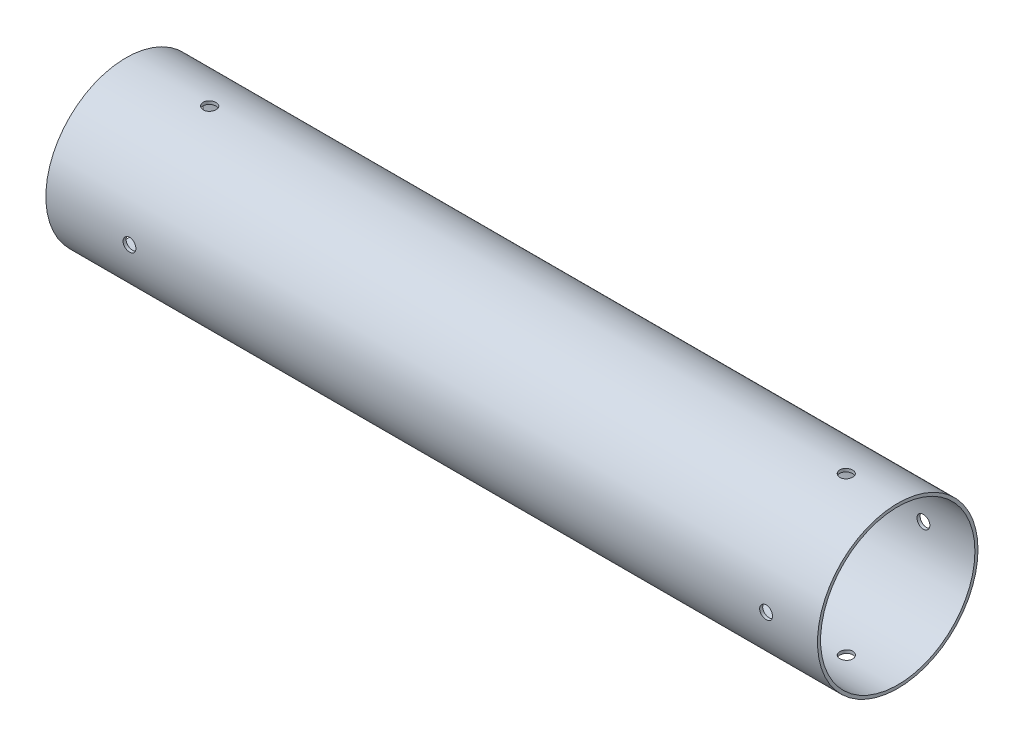
SolidWorks part; units mm, degrees
ref_plane "Front Plane" through (0, 0, 0) normal (1, 0, 0) x (0, 1, 0)
ref_plane "Top Plane" through (0, 0, 0) normal (0, 0, 1) x (0, 1, 0)
ref_plane "Right Plane" through (0, 0, 0) normal (0, 1, 0) x (-1, 0, 0)
sketch "Sketch1" plane through (0, 0, 0) normal (1, 0, 0) x (0, 1, 0)
  circle A0 centre (0, 0) radius 39.624
  circle A1 centre (0, 0) radius 38.1
  dimension "D1" = 79.248
  dimension "D2" = 76.2
extrude "Boss-Extrude1" add sketch "Sketch1" along normal blind 381
sketch "Sketch2" plane through (0, 0, 0) normal (0, 1, 0) x (-1, 0, 0)
  line L0 (-381, 39.624) -> (-381, -39.624) construction
  line L1 (-355.6, 0) -> (-381, 0) construction
  circle A0 centre (-355.6, 0) radius 3.175
  dimension "D1" = 6.35
  dimension "D2" = 25.4
extrude "Cut-Extrude1" cut sketch "Sketch2" along normal through all
pattern_circular "CirPattern1" count 4 over 360 about axis through (381, 0, 0) along (-1, 0, 0) of "Cut-Extrude1"
sketch "Sketch3" plane through (0, 0, 0) normal (0, 1, 0) x (-1, 0, 0)
  circle A0 centre (-41.275, 0) radius 3.175
  dimension "D1" = 6.35
  dimension "D2" = 41.275
extrude "Cut-Extrude2" cut sketch "Sketch3" along normal through all
pattern_circular "CirPattern2" count 4 over 360 about axis through (381, 0, 0) along (-1, 0, 0) of "Cut-Extrude2"
